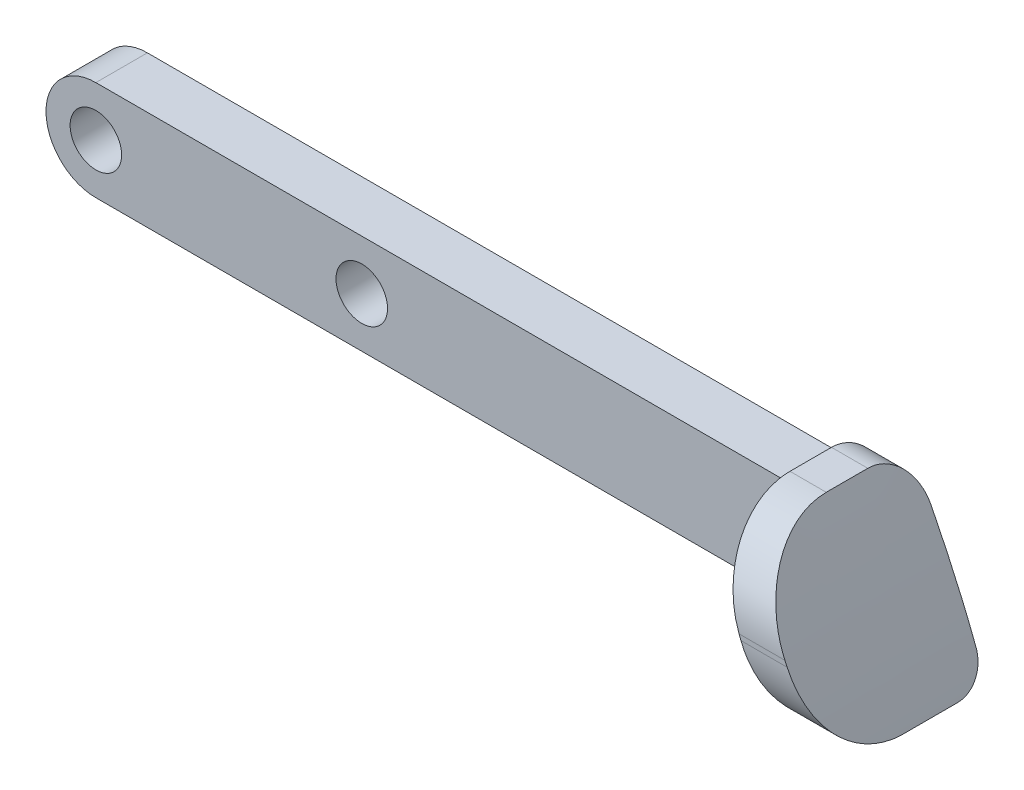
SolidWorks part; units mm, degrees
ref_plane "前视基准面" through (0, 0, 0) normal (0, 0, 1) x (1, 0, 0)
ref_plane "上视基准面" through (0, 0, 0) normal (0, 1, 0) x (1, 0, 0)
ref_plane "右视基准面" through (0, 0, 0) normal (1, 0, 0) x (0, 0, -1)
other "Configuration Table"
sketch "草图1" plane through (0, 0, 0) normal (0, 0, 1) x (1, 0, 0)
  line L0 (0, 0) -> (16, 0) construction
  line L1 (0, 3) -> (50, 3)
  line L2 (0, -3) -> (50, -3)
  line L3 (50, 3) -> (50, -3)
  circle A0 centre (0, 0) radius 1.55
  circle A1 centre (16, 0) radius 1.55
  arc A2 (0, 3) -> (0, -3) centre (0, 0) ccw
  dimension "D1" = 3
  dimension "D2" = 3.1
  dimension "D4" = 50
  dimension "D5" = 6
  dimension "D7" = 50
  dimension "D6" = 3.1
  dimension "D3" = 16
extrude "凸台-拉伸1" add sketch "草图1" along normal blind 3.1
sketch "草图3" plane through (0, 0, 0) normal (0, 0, -1) x (-1, 0, 0)
  line L0 (-44.9354, 4.0172) -> (-56.2342, 4.0172)
  line L1 (-56.2342, 4.0172) -> (-56.2342, -3.4932)
  line L2 (-56.2342, -3.4932) -> (-47.4852, -3.4932)
  spline S0 degree 2 poles (-44.9354, 4.0172) (-46.9905, 0.5176) (-47.4852, -3.4932) knots 0 0 0 1 1 1
extrude "切除-拉伸1" cut sketch "草图3" against normal blind 10
sketch "草图4" plane through (0, 0, 0) normal (0, 0, -1) x (-1, 0, 0)
  line L0 (-45.8446, 5.5252) -> (-43.6608, 5.5252)
  line L1 (-43.6608, 5.5252) -> (-47.6508, -4.7689)
  line L2 (-47.6508, -4.7689) -> (-50.4632, -4.7689)
  line L5 (0, 3) -> (-45.4942, 3) construction
  line L6 (0, -3) -> (-47.4182, -3) construction
  spline S0 degree 3 poles (-45.8446, 5.5252) (-47.6225, 2.2124) (-49.2891, -1.1892) (-50.4632, -4.7689) knots 0 0 0 0 1 1 1 1
  dimension "D3" = 11.2975
  dimension "D1" = 2.5252
  dimension "D2" = 1.7689
  dimension "D4" = 11.0403
  dimension "D5" = 0.2326
extrude "凸台-拉伸2" add sketch "草图4" against normal blind 10
fillet "圆角2" radius 5 2 edges at (49.057, -4.7689, 10) (44.7527, 5.5252, 10)
fillet "圆角3" radius 2.5 1 edges at (44.7527, 5.5252, 0)
fillet "圆角4" radius 1.7 1 edges at (49.057, -4.7689, 0)
